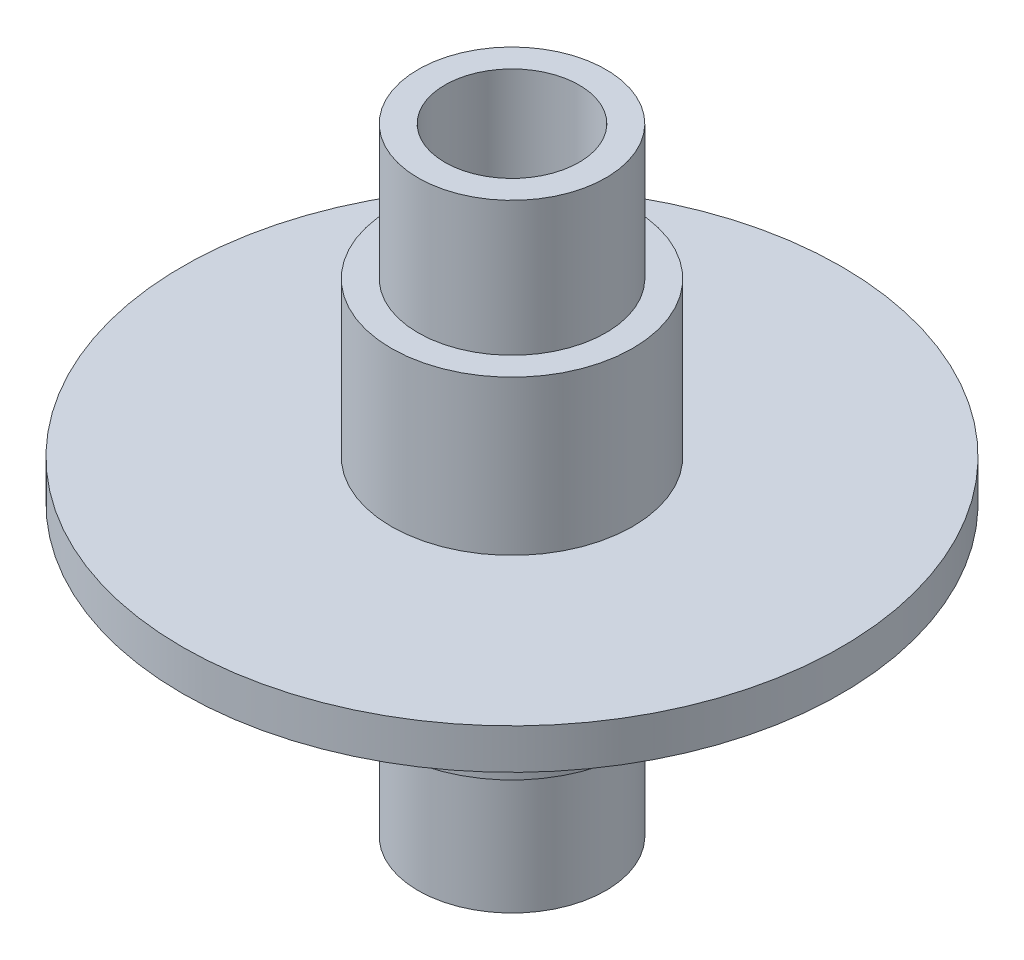
SolidWorks part; units mm, degrees
ref_plane "Front Plane" through (0, 0, 0) normal (0, 0, 1) x (1, 0, 0)
ref_plane "Top Plane" through (0, 0, 0) normal (0, 1, 0) x (1, 0, 0)
ref_plane "Right Plane" through (0, 0, 0) normal (1, 0, 0) x (0, 0, -1)
sketch "Sketch1" plane through (0, 0, 0) normal (0, 0, 1) x (1, 0, 0)
  line L0 (0, 17.7244) -> (0, -16.5858) construction
  line L4 (-9, -6.7937) -> (-24.5611, -6.7937)
  line L5 (-24.5611, -6.7937) -> (-24.5611, -9.7937)
  line L13 (-5, -31.2937) -> (-5, 14.7063)
  line L14 (-5, 14.7063) -> (-7, 14.7063)
  line L15 (-7, 14.7063) -> (-7, 4.7063)
  line L16 (-7, 4.7063) -> (-9, 4.7063)
  line L17 (-9, 4.7063) -> (-9, -6.7937)
  line L18 (-5, -31.2937) -> (-7, -31.2937)
  line L19 (-7, -31.2937) -> (-7, -21.2937)
  line L20 (-9, -21.2937) -> (-9, -9.7937)
  line L21 (-9, -9.7937) -> (-24.5611, -9.7937)
  line L22 (-7, -21.2937) -> (-9, -21.2937)
  dimension "D1" = 10
  dimension "D3" = 14
  dimension "D4" = 10
  dimension "D5" = 18
revolve "Revolve1" add sketch "Sketch1" angle 360 about L0
